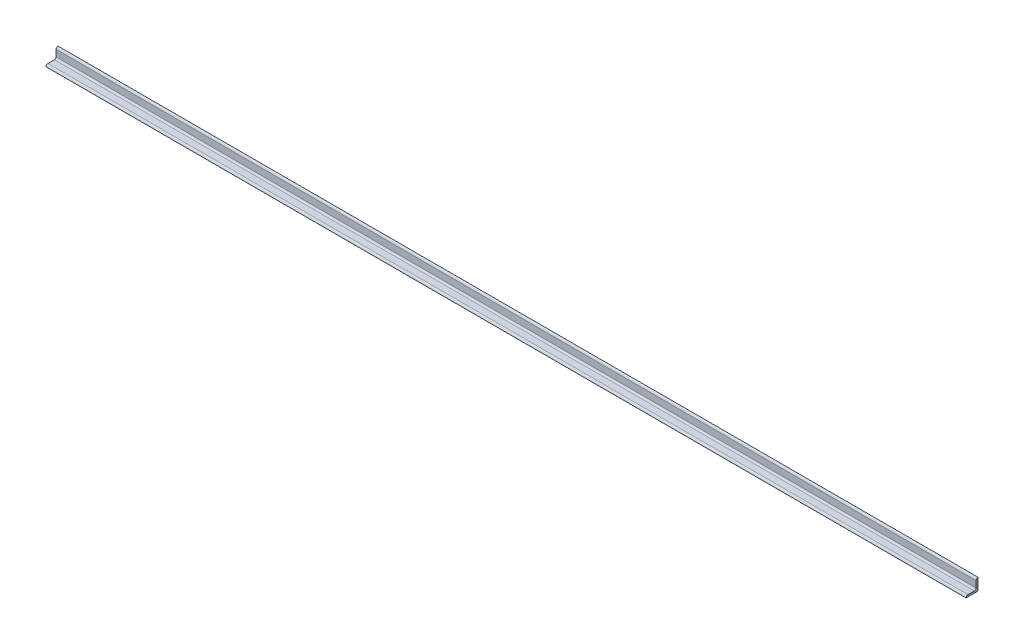
SolidWorks part; units mm, degrees
ref_plane "Alzado" through (0, 0, 0) normal (0, 0, 1) x (1, 0, 0)
ref_plane "Planta" through (0, 0, 0) normal (0, 1, 0) x (1, 0, 0)
ref_plane "Vista lateral" through (0, 0, 0) normal (1, 0, 0) x (0, 0, -1)
sketch "Croquis2" plane through (0, 0, 0) normal (0, 0, 1) x (1, 0, 0)
  line L0 (-960, 0) -> (960, 0)
  dimension "D1" = 1920
other "Miembro estructural1"
ref_plane "Plano1" through (-960, 0, 0) normal (1, 0, 0) x (0, 1, 0)
sketch "Sketch1" plane through (-960, 0, 0) normal (1, 0, 0) x (0, 1, 0)
  line L0 (0, 0) -> (0, 25)
  line L1 (0, 12.5) -> (4, 12.5) construction
  line L2 (4, 21) -> (4, 7.5)
  line L3 (7.5, 4) -> (21, 4)
  line L4 (12.5, 4) -> (12.5, 0) construction
  line L5 (25, 0) -> (0, 0)
  arc A0 (25, 0) -> (21, 4) centre (21, 0) ccw
  arc A1 (0, 25) -> (4, 21) centre (0, 21) cw
  arc A2 (7.5, 4) -> (4, 7.5) centre (7.5, 7.5) cw
  point P10 (12.5, 0)
  point P14 (0, 12.5)
  point P15 (4, 12.5)
  point P16 (12.5, 4)
  point P17 (4, 25)
  point P18 (25, 4)
  point P21 (0, 0)
  dimension "D2" = 4
  dimension "D3" = 25
  dimension "Radius_1" = 3.5
  dimension "D1" = 4
